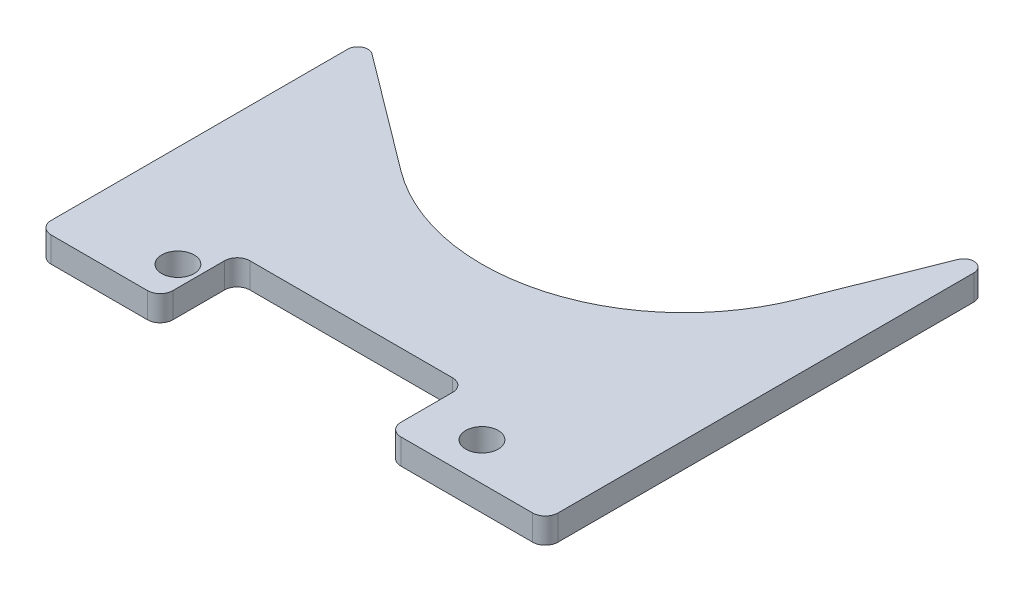
SolidWorks part; units mm, degrees
ref_plane "Front Plane" through (0, 0, 0) normal (0, 0, 1) x (1, 0, 0)
ref_plane "Top Plane" through (0, 0, 0) normal (0, 1, 0) x (1, 0, 0)
ref_plane "Right Plane" through (0, 0, 0) normal (1, 0, 0) x (0, 0, -1)
sketch "Sketch1" plane through (0, 0, 0) normal (0, 1, 0) x (1, 0, 0)
  line L1 (-31.75, 30.1625) -> (31.75, 30.1625)
  line L2 (-31.75, 30.1625) -> (-31.75, -30.1625)
  line L3 (-31.75, -30.1625) -> (31.75, -30.1625)
  line L4 (31.75, 30.1625) -> (31.75, -30.1625)
  line L5 (-31.75, 30.1625) -> (31.75, -30.1625) construction
  line L6 (-31.75, -30.1625) -> (31.75, 30.1625) construction
  point P0 (0, 0)
  dimension "D1" = 63.5
  dimension "D2" = 60.325
extrude "Boss-Extrude1" add sketch "Sketch1" along normal blind 3.175
sketch "Sketch2" plane through (0, 0, 0) normal (0, -1, 0) x (-1, 0, 0)
  line L0 (31.75, -30.1625) -> (-31.75, -30.1625) construction
  line L1 (-19.05, -25.4) -> (-31.75, -25.4) construction
  line L2 (-31.75, -30.1625) -> (-31.75, 30.1625) construction
  line L3 (19.05, -25.4) -> (31.75, -25.4) construction
  line L4 (31.75, 30.1625) -> (31.75, -30.1625) construction
  circle A0 centre (-19.05, -25.4) radius 2.032
  circle A1 centre (19.05, -25.4) radius 2.032
  dimension "D2" = 4.064
  dimension "D1" = 4.7625
  dimension "D3" = 38.1
extrude "Cut-Extrude1" cut sketch "Sketch2" against normal through all
sketch "Sketch3" plane through (0, 3.175, 0) normal (0, 1, 0) x (1, 0, 0)
  line L0 (-31.75, -30.1625) -> (31.75, -30.1625) construction
  line L1 (-16.51, -30.1625) -> (12.065, -30.1625)
  line L2 (-16.51, -30.1625) -> (-16.51, -20.5105)
  line L3 (-16.51, -20.5105) -> (12.065, -20.5105)
  line L4 (12.065, -30.1625) -> (12.065, -20.5105)
  line L5 (-31.75, 30.1625) -> (-31.75, -30.1625) construction
  dimension "D1" = 15.24
  dimension "D2" = 28.575
  dimension "D3" = 9.652
extrude "Cut-Extrude2" cut sketch "Sketch3" against normal through all
fillet "Fillet1" radius 1.5875 6 edges at (-31.75, 1.5875, 30.1625) (-16.51, 1.5875, 30.1625) (-16.51, 1.5875, 20.5105) (12.065, 1.5875, 20.5105) (12.065, 1.5875, 30.1625) (31.75, 1.5875, 30.1625)
sketch "Sketch5" plane through (0, 3.175, 0) normal (0, 1, 0) x (1, 0, 0)
  line L4 (-15.24, -1.27) -> (-31.75, 11.1125)
  line L5 (-31.75, 30.1625) -> (-31.75, -28.575) construction
  line L6 (23.6037, 9.6679) -> (31.75, 30.1625)
  line L7 (-31.75, 11.1125) -> (-31.75, 30.1625)
  line L8 (-31.75, 30.1625) -> (31.75, 30.1625)
  line L9 (31.75, -28.575) -> (31.75, 30.1625) construction
  line L10 (-30.1625, -30.1625) -> (-18.0975, -30.1625) construction
  arc A1 (-15.24, -1.27) -> (23.6037, 9.6679) centre (0, 19.05) ccw
  dimension "D1" = 50.8
  dimension "D2" = 19.05
  dimension "D3" = 60.325
  dimension "D4" = 19.05
extrude "Cut-Extrude4" cut sketch "Sketch5" against normal through all
fillet "Fillet2" radius 1.27 2 edges at (31.75, 1.5875, -30.1625) (-31.75, 1.5875, -11.1125)
